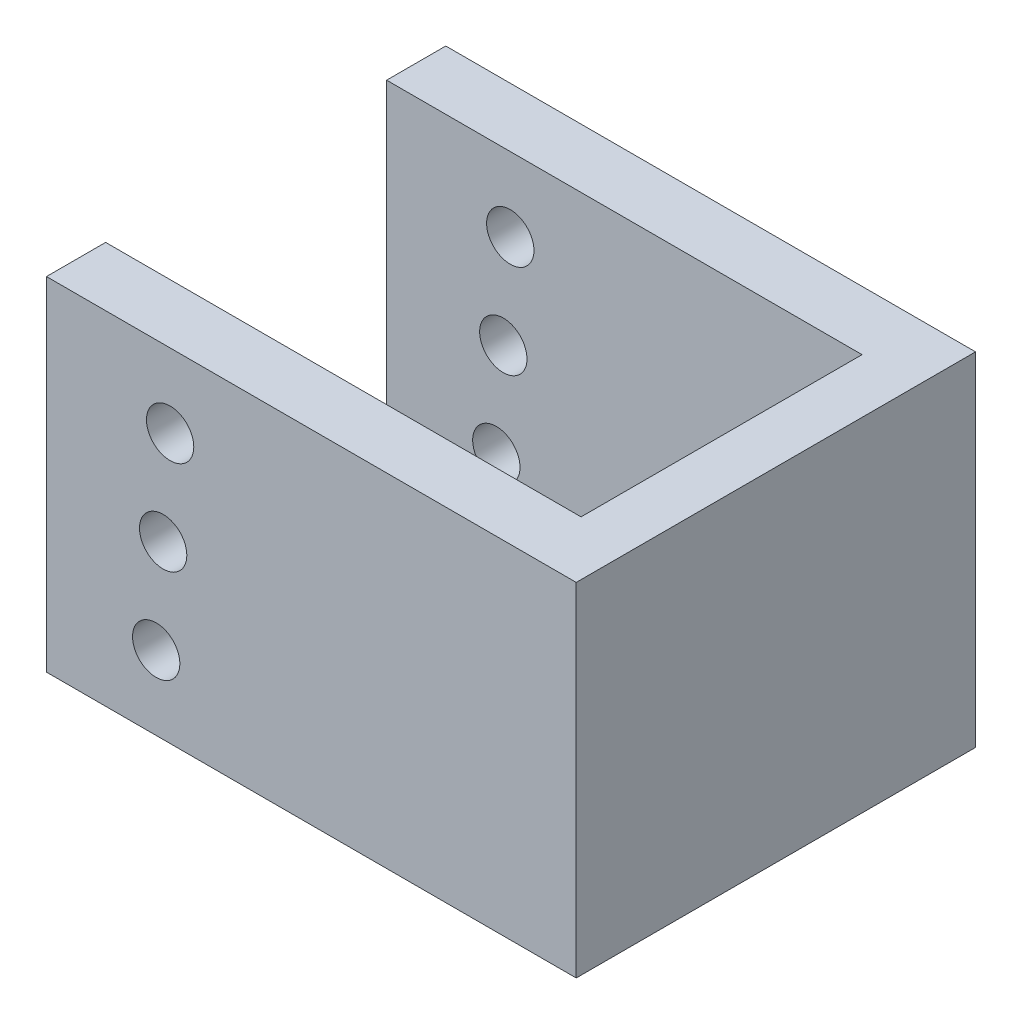
SolidWorks part; units mm, degrees
ref_plane "Alzado" through (0, 0, 0) normal (0, 0, 1) x (1, 0, 0)
ref_plane "Planta" through (0, 0, 0) normal (0, 1, 0) x (1, 0, 0)
ref_plane "Vista lateral" through (0, 0, 0) normal (1, 0, 0) x (0, 0, -1)
sketch "Croquis1" plane through (0, 0, -8.1) normal (0, 0, 1) x (1, 0, 0)
  line L0 (-4.5629, -53.4081) -> (-6.5002, -64.9913)
  line L1 (-20.6364, -53.4081) -> (-20.6364, -64.9913)
  line L2 (-21.8816, 0.8244) -> (-20.426, -62.5717) construction
  line L3 (-20.6364, -64.9913) -> (-6.5002, -64.9913)
  line L5 (-4.5629, -53.4081) -> (-20.6364, -53.4081)
  line L6 (-16.4562, -55.9081) -> (-16.4562, -53.4081) construction
  line L7 (-16.9269, -62.4913) -> (-16.9269, -64.9913) construction
  line L8 (-16.6916, -59.1997) -> (-16.9269, -62.4913) construction
  line L9 (-16.6916, -59.1997) -> (-16.4562, -55.9081) construction
  line L10 (-13.4749, -63.0687) -> (-3.0143, -0.5246) construction
  circle A0 centre (-16.4562, -55.9081) radius 1 construction
  circle A1 centre (-16.6916, -59.1997) radius 1 construction
  circle A2 centre (-16.9269, -62.4913) radius 1 construction
  dimension "D2" = 2
  dimension "D1" = 2.5
extrude "Saliente-Extruir1" add sketch "Croquis1" along normal blind 2
sketch "Croquis2" plane through (0, 0, -6.1) normal (0, 0, 1) x (1, 0, 0)
  line L0 (-4.5629, -53.4081) -> (-2.7265, -53.4081)
  line L1 (-2.7265, -53.4081) -> (-2.7265, -64.9913)
  line L2 (-2.7265, -64.9913) -> (-6.5002, -64.9913)
  line L3 (-6.5002, -64.9913) -> (-4.5629, -53.4081)
extrude "Saliente-Extruir2" add sketch "Croquis2" against normal blind 11.5
sketch "Croquis3" plane through (0, 0, -17.6) normal (0, 0, -1) x (-1, 0, 0)
  line L0 (2.7265, -53.4081) -> (20.6364, -53.4081)
  line L1 (20.6364, -53.4081) -> (20.6364, -64.9913)
  line L2 (20.6364, -64.9913) -> (2.7265, -64.9913)
  line L3 (2.7265, -64.9913) -> (2.7265, -53.4081)
extrude "Saliente-Extruir3" add sketch "Croquis3" along normal blind 2
hole_wizard "Taladro roscado M21" positions "Croquis4" profile "Croquis5" tap size "M2" standard "ISO"
sketch "Croquis4" plane through (0, 0, -6.1) normal (0, 0, 1) x (1, 0, 0)
  point P0 (-16.9269, -62.4913)
  point P3 (-16.6916, -59.1997)
  point P6 (-16.4562, -55.9081)
sketch "Croquis5" plane through (-16.9269, -62.4913, -6.1) normal (1, 0, 0) x (0, -1, 0)
  line L0 (0, 0) -> (0, 17.4807)
  line L1 (0, 17.4807) -> (0.8, 17)
  line L2 (0.8, 17) -> (0.8, 0)
  line L5 (0.8, 0) -> (0, 0)
  line L10 (0, 17.4807) -> (-0.8, 17) construction
  line L11 (0, -6.35) -> (0, 107.95) construction
  dimension "Diámetro de perforador para roscar" = 1.6
  dimension "Profundidad de perforador para roscar" = 17
  dimension "Ángulo de perforador" = 118
